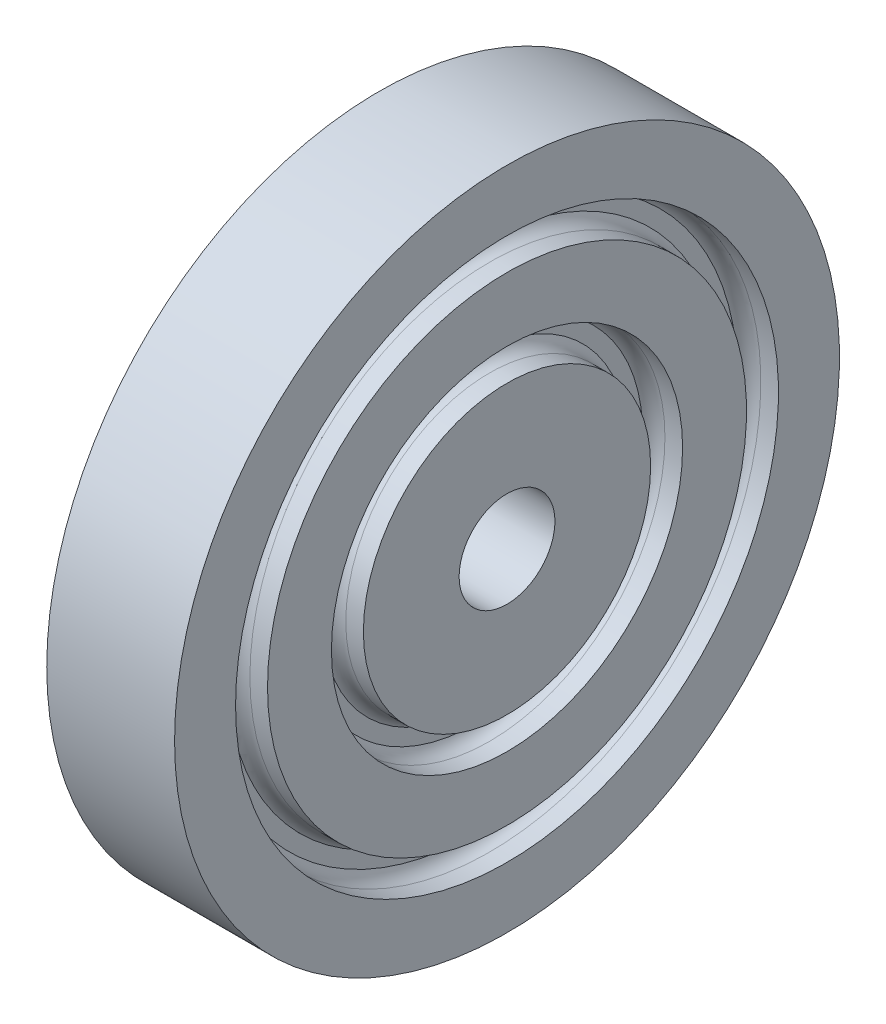
SolidWorks part; units mm, degrees
ref_plane "Front Plane" through (0, 0, 0) normal (0, 0, 1) x (1, 0, 0)
ref_plane "Top Plane" through (0, 0, 0) normal (0, 1, 0) x (1, 0, 0)
ref_plane "Right Plane" through (0, 0, 0) normal (1, 0, 0) x (0, 0, -1)
sketch "Sketch1" plane through (0, 0, 0) normal (0, 0, 1) x (1, 0, 0)
  line L0 (0, 0.9849) -> (0, -1.2409)
  line L1 (0, 0.9849) -> (1, 0.9849)
  line L2 (1, 0.9849) -> (1, -1.2409)
  line L3 (1, -1.2409) -> (0, -1.2409)
  line L4 (0, 0.122) -> (1, 0.122)
  line L5 (0, -0.128) -> (1, -0.128)
  line L6 (-1.0713, -1.6156) -> (2.4197, -1.6156) construction
  line L7 (0, 0.5079) -> (0.138, 0.5079)
  line L8 (0.25, 0.4383) -> (0.25, 0.3203)
  line L9 (0.138, 0.2579) -> (0, 0.2579)
  line L10 (0.138, 0.5079) -> (0.138, 0.2579)
  line L12 (0.862, 0.2579) -> (1, 0.2579)
  line L13 (0.75, 0.4383) -> (0.75, 0.3203)
  line L14 (0.862, 0.5079) -> (0.862, 0.2579)
  line L15 (1, 0.5079) -> (0.862, 0.5079)
  line L16 (0.862, -0.2421) -> (1, -0.2421)
  line L17 (0.862, -0.4921) -> (0.862, -0.2421)
  line L18 (0.75, -0.4225) -> (0.75, -0.3045)
  line L19 (1, -0.4921) -> (0.862, -0.4921)
  line L20 (0, -0.518) -> (0.1462, -0.5178)
  line L21 (0.1462, -0.268) -> (0, -0.268)
  line L22 (0.1462, -0.5178) -> (0.1462, -0.268)
  line L23 (0.2521, -0.4439) -> (0.2521, -0.3339)
  arc A0 (0.138, 0.5079) -> (0.25, 0.4383) centre (0.138, 0.3829) cw
  arc A1 (0.138, 0.2579) -> (0.25, 0.3203) centre (0.138, 0.3897) ccw
  arc A2 (0.862, 0.2579) -> (0.75, 0.3203) centre (0.862, 0.3897) cw
  arc A3 (0.862, 0.5079) -> (0.75, 0.4383) centre (0.862, 0.3829) ccw
  arc A4 (0.862, -0.2421) -> (0.75, -0.3045) centre (0.862, -0.3739) ccw
  arc A5 (0.862, -0.4921) -> (0.75, -0.4225) centre (0.862, -0.3671) cw
  arc A6 (0.1462, -0.5178) -> (0.2521, -0.4439) centre (0.1379, -0.3931) ccw
  arc A7 (0.1462, -0.268) -> (0.2521, -0.3339) centre (0.1378, -0.3995) cw
  point P29 (0.75, 0.3793)
  point P46 (0.75, -0.3635)
  point P47 (1, -0.128)
  dimension "D3" = 0.125
  dimension "D4" = 0.1318
  dimension "D1" = 1
  dimension "D2" = 0.25
  dimension "D5" = 0.25
  dimension "D6" = 0.5
  dimension "D7" = 0.1359
  dimension "D8" = 0.14
  dimension "D9" = 0.25
revolve "Revolve1" add sketch "Sketch1" angle 360 about L6
